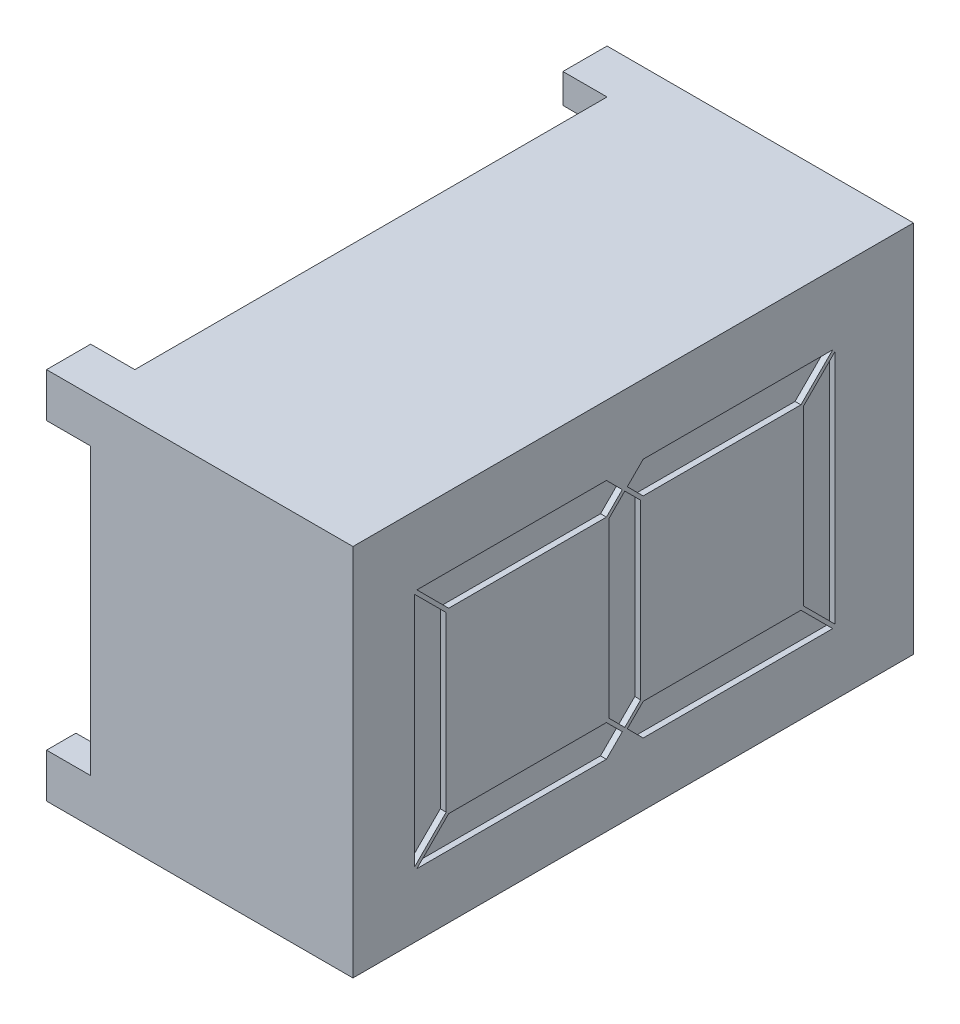
SolidWorks part; units mm, degrees
ref_plane "Front Plane" through (0, 0, 0) normal (1, 0, 0) x (0, 1, 0)
ref_plane "Top Plane" through (0, 0, 0) normal (0, 0, 1) x (0, 1, 0)
ref_plane "Right Plane" through (0, 0, 0) normal (0, 1, 0) x (-1, 0, 0)
sketch "Sketch1" plane through (0, 0, 0) normal (1, 0, 0) x (0, 1, 0)
  line L1 (4.175, 0.3159) -> (16.875, 0.3159)
  line L2 (4.175, 0.3159) -> (4.175, -18.7341)
  line L3 (4.175, -18.7341) -> (16.875, -18.7341)
  line L4 (16.875, 0.3159) -> (16.875, -18.7341)
  dimension "D1" = 19.05
  dimension "D2" = 12.7
extrude "Boss-Extrude1" add sketch "Sketch1" along normal blind 10.414
sketch "Sketch2" plane through (0, 0, 0) normal (-1, 0, 0) x (0, -1, 0)
  line L12 (-5.175, -17.7341) -> (-5.175, -0.6841)
  line L13 (-5.175, -0.6841) -> (-15.875, -0.6841)
  line L14 (-15.875, -0.6841) -> (-15.875, -17.7341)
  line L15 (-15.875, -17.7341) -> (-5.175, -17.7341)
  line L16 (-5.175, -17.7341) -> (-5.175, -0.6841)
  line L17 (-5.175, -0.6841) -> (-15.875, -0.6841)
  line L18 (-15.875, -0.6841) -> (-15.875, -17.7341)
  line L19 (-15.875, -17.7341) -> (-5.175, -17.7341)
  dimension "D1" = 1
extrude "Cut-Extrude1" cut sketch "Sketch2" against normal blind 2.414
sketch "Sketch4" plane through (0, 16.875, 0) normal (0, 1, 0) x (-1, 0, 0)
  line L2 (-10.414, -1.1841) -> (0, -1.1841)
  line L3 (-1.5, -1.1841) -> (0, -1.1841)
  line L5 (-10.414, -17.2341) -> (0, -17.2341)
  line L6 (-1.5, -17.2341) -> (0, -17.2341)
  line L7 (0, -1.1841) -> (0, -17.2341)
  line L8 (-1.5, -18.7341) -> (-1.5, 0.3159)
  line L9 (-1.5, -17.2341) -> (-1.5, -1.1841)
  dimension "D1" = 1.5
  dimension "D2" = 1.5
  dimension "D3" = 1.5
extrude "Cut-Extrude2" cut sketch "Sketch4" against normal blind 42.414
sketch "Sketch5" plane through (0, 0, -18.7341) normal (0, 0, -1) x (1, 0, 0)
  line L6 (10.414, -5.675) -> (0, -5.675)
  line L7 (1.5, -5.675) -> (0, -5.675)
  line L9 (10.414, -15.375) -> (0, -15.375)
  line L10 (1.5, -15.375) -> (0, -15.375)
  line L11 (0, -5.675) -> (0, -15.375)
  line L12 (1.5, -4.175) -> (1.5, -16.875)
  line L13 (1.5, -5.675) -> (1.5, -15.375)
  dimension "D1" = 1.5
  dimension "D2" = 1.5
  dimension "D3" = 1.5
extrude "Cut-Extrude3" cut sketch "Sketch5" against normal blind 42.414
sketch "Sketch6" plane through (10.414, 0, 0) normal (1, 0, 0) x (0, 1, 0)
  line L2 (7.4718, -14.9941) -> (13.3476, -14.9941)
  line L3 (14.4276, -1.7725) -> (6.3918, -1.7725)
  line L17 (13.3476, -14.9941) -> (14.4276, -16.0741)
  line L18 (6.3918, -16.0741) -> (14.4276, -16.0741)
  line L22 (7.4718, -14.9941) -> (6.3918, -16.0741)
  line L23 (13.4325, -14.9093) -> (13.4325, -9.5482)
  line L27 (13.9725, -9.0082) -> (13.4325, -9.5482)
  line L30 (13.9725, -9.0082) -> (14.5125, -9.5482)
  line L31 (14.5125, -15.9893) -> (14.5125, -9.5482)
  line L33 (13.4325, -14.9093) -> (14.5125, -15.9893)
  line L44 (7.4718, -2.8525) -> (6.3918, -1.7725)
  line L45 (13.3476, -2.8525) -> (7.4718, -2.8525)
  line L46 (13.3476, -2.8525) -> (14.4276, -1.7725)
  line L47 (7.3869, -2.9374) -> (6.3069, -1.8574)
  line L48 (6.3069, -1.8574) -> (6.3069, -8.2985)
  line L49 (6.8469, -8.8385) -> (6.3069, -8.2985)
  line L50 (6.8469, -8.8385) -> (7.3869, -8.2985)
  line L51 (7.3869, -2.9374) -> (7.3869, -8.2985)
  line L52 (13.4325, -2.9374) -> (14.5125, -1.8574)
  line L53 (14.5125, -8.2985) -> (14.5125, -1.8574)
  line L54 (13.9725, -8.8385) -> (14.5125, -8.2985)
  line L55 (13.4325, -8.2985) -> (13.9725, -8.8385)
  line L56 (13.4325, -8.2985) -> (13.4325, -2.9374)
  line L57 (7.4718, -8.3833) -> (13.3476, -8.3833)
  line L58 (13.3476, -8.3833) -> (13.8876, -8.9233)
  line L59 (13.8876, -8.9233) -> (13.3476, -9.4633)
  line L60 (7.4718, -9.4633) -> (13.3476, -9.4633)
  line L61 (6.9318, -8.9233) -> (7.4718, -9.4633)
  line L62 (6.9318, -8.9233) -> (7.4718, -8.3833)
  line L63 (6.8469, -9.0082) -> (6.3069, -9.5482)
  line L64 (6.3069, -9.5482) -> (6.3069, -15.9893)
  line L65 (7.3869, -14.9093) -> (6.3069, -15.9893)
  line L66 (7.3869, -9.5482) -> (7.3869, -14.9093)
  line L67 (6.8469, -9.0082) -> (7.3869, -9.5482)
extrude "Cut-Extrude4" cut sketch "Sketch6" against normal blind 0.2
